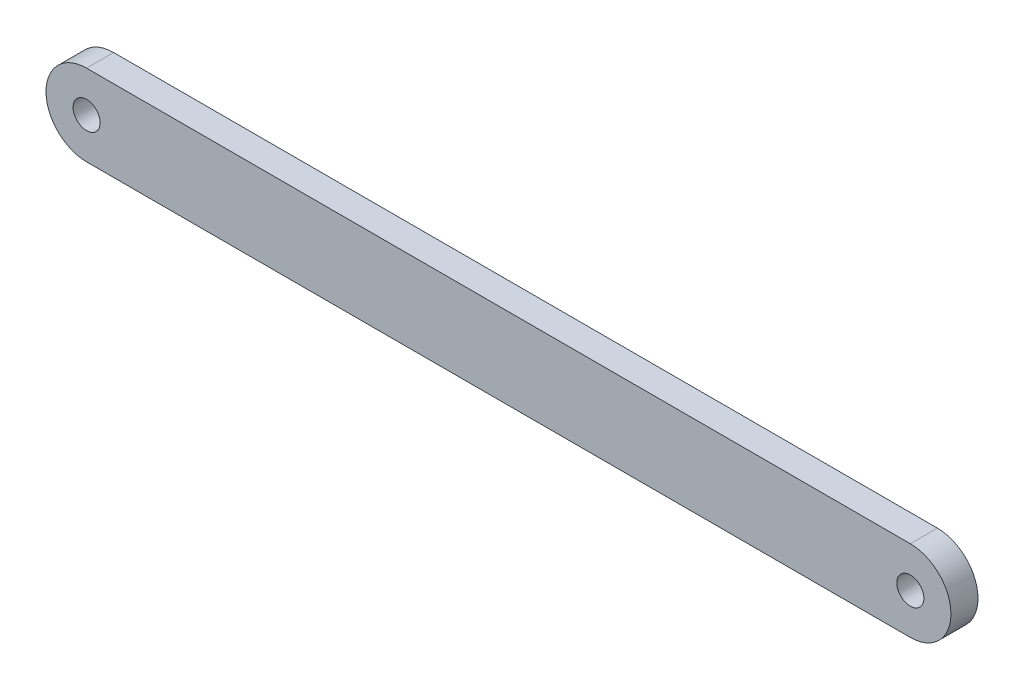
SolidWorks part; units mm, degrees
ref_plane "Front Plane" through (0, 0, 0) normal (0, 0, 1) x (1, 0, 0)
ref_plane "Top Plane" through (0, 0, 0) normal (0, 1, 0) x (1, 0, 0)
ref_plane "Right Plane" through (0, 0, 0) normal (1, 0, 0) x (0, 0, -1)
sketch "Sketch1" plane through (0, 0, 0) normal (0, 0, 1) x (1, 0, 0)
  line L0 (0, 0) -> (152.204, 0) construction
  line L1 (0, 7.5) -> (152.204, 7.5)
  line L2 (0, -7.5) -> (152.204, -7.5)
  arc A0 (0, 7.5) -> (0, -7.5) centre (0, 0) ccw
  arc A1 (152.204, -7.5) -> (152.204, 7.5) centre (152.204, 0) ccw
  circle A2 centre (0, 0) radius 2.5
  circle A3 centre (152.204, 0) radius 2.5
  point P3 (76.102, 0)
  dimension "D2" = 7.5
  dimension "D3" = 5
  dimension "D1" = 152.204
extrude "Boss-Extrude1" add sketch "Sketch1" along normal blind 5
